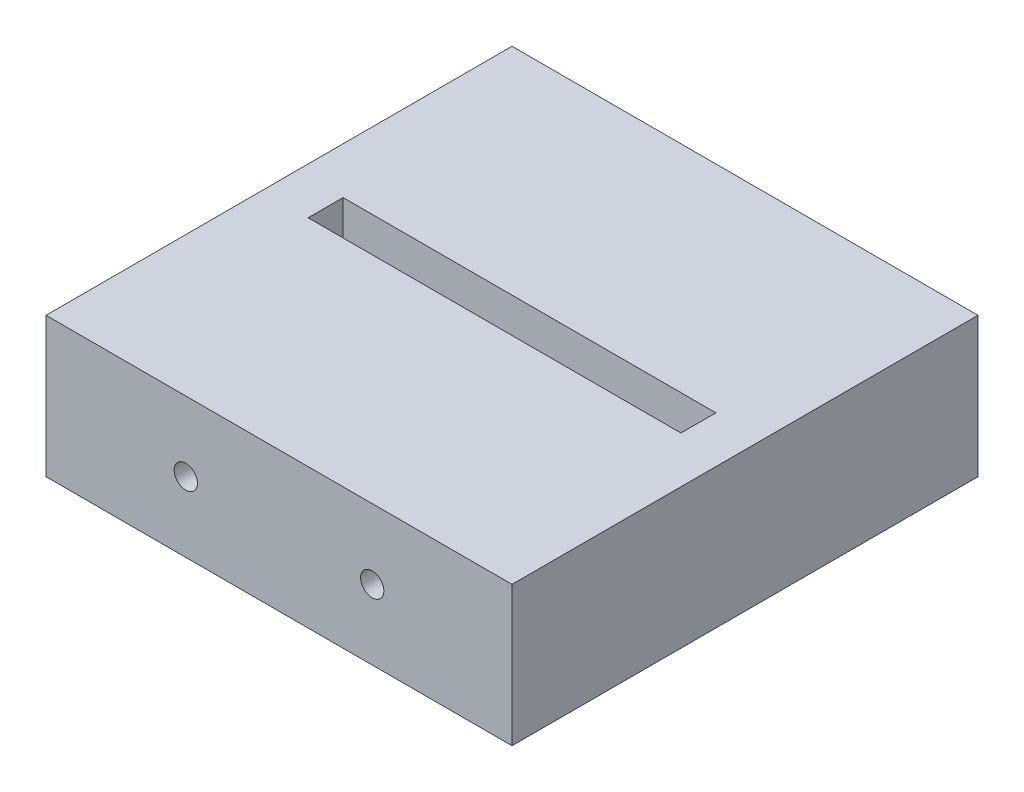
SolidWorks part; units mm, degrees
ref_plane "Front Plane" through (0, 0, 0) normal (0, 0, 1) x (1, 0, 0)
ref_plane "Top Plane" through (0, 0, 0) normal (0, 1, 0) x (1, 0, 0)
ref_plane "Right Plane" through (0, 0, 0) normal (1, 0, 0) x (0, 0, -1)
sketch "Sketch1" plane through (0, 0, 0) normal (0, 1, 0) x (1, 0, 0)
  line L1 (63.5, -63.5) -> (-63.5, -63.5)
  line L2 (63.5, -63.5) -> (63.5, 63.5)
  line L3 (63.5, 63.5) -> (-63.5, 63.5)
  line L4 (-63.5, -63.5) -> (-63.5, 63.5)
  line L5 (63.5, -63.5) -> (-63.5, 63.5) construction
  line L6 (63.5, 63.5) -> (-63.5, -63.5) construction
  point P0 (0, 0)
  dimension "D1" = 127
  dimension "D2" = 127
extrude "Boss-Extrude1" add sketch "Sketch1" along normal blind 38.1
sketch "Sketch2" plane through (0, 0, 0) normal (0, -1, 0) x (-1, 0, 0)
  line L1 (-50.8, -4.7625) -> (50.8, -4.7625)
  line L2 (-50.8, -4.7625) -> (-50.8, 4.7625)
  line L3 (-50.8, 4.7625) -> (50.8, 4.7625)
  line L4 (50.8, -4.7625) -> (50.8, 4.7625)
  line L5 (-50.8, -4.7625) -> (50.8, 4.7625) construction
  line L6 (-50.8, 4.7625) -> (50.8, -4.7625) construction
  point P0 (0, 0)
  dimension "D1" = 9.525
  dimension "D2" = 101.6
extrude "Cut-Extrude1" cut sketch "Sketch2" against normal through all
sketch "Sketch3" plane through (0, 0, 63.5) normal (0, 0, 1) x (1, 0, 0)
  line L0 (-63.5, 0) -> (63.5, 0) construction
  line L2 (0, 0) -> (0, 38.1)
  line L3 (-63.5, 38.1) -> (63.5, 38.1) construction
  circle A0 centre (-25.4, 19.05) radius 3.175
  circle A1 centre (25.4, 19.05) radius 3.175
  dimension "D1" = 6.35
  dimension "D2" = 19.05
  dimension "D3" = 25.4
extrude "Cut-Extrude2" cut sketch "Sketch3" against normal through all contours A0 | A1
